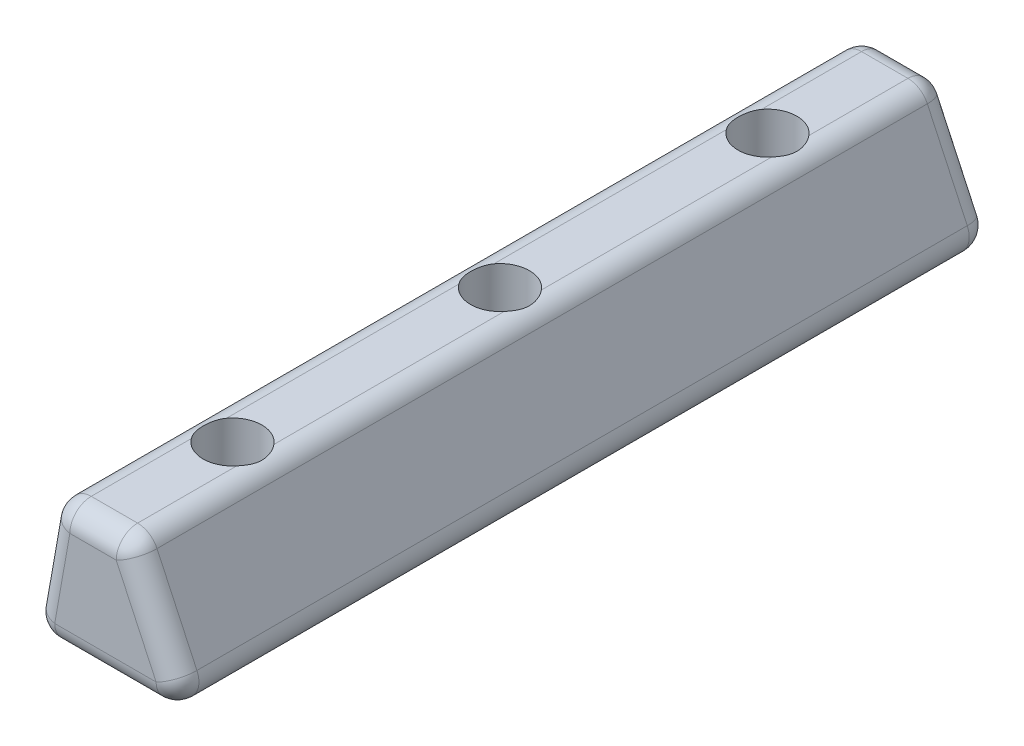
SolidWorks part; units mm, degrees
material "ABS"
ref_plane "前视基准面" through (0, 0, 0) normal (0, 0, 1) x (1, 0, 0)
ref_plane "上视基准面" through (0, 0, 0) normal (0, 1, 0) x (1, 0, 0)
ref_plane "右视基准面" through (0, 0, 0) normal (1, 0, 0) x (0, 0, -1)
other "Configuration Table"
sketch "草图1" plane through (0, 0, 0) normal (0, 0, 1) x (1, 0, 0)
  line L0 (0, 0) -> (15, 0)
  line L1 (15, 0) -> (9.4043, 12)
  line L2 (9.4043, 12) -> (2.1159, 12)
  line L3 (2.1159, 12) -> (0, 0)
  dimension "D1" = 15
  dimension "D2" = 80
  dimension "D3" = 65
  dimension "D4" = 12
extrude "凸台-拉伸1" add sketch "草图1" along normal blind 76
sketch "草图2" plane through (0, 0, 0) normal (0, -1, 0) x (1, 0, 0)
  line L0 (0, 38) -> (15, 38) construction
  line L3 (0, 76) -> (0, 0) construction
  line L6 (15, 76) -> (15, 0) construction
  circle A0 centre (6, 63) radius 1.55
  circle A1 centre (6, 13) radius 1.55
  circle A2 centre (6, 38) radius 1.55
  dimension "D1" = 3.1
  dimension "D2" = 3.1
  dimension "D3" = 3.1
  dimension "D4" = 25
  dimension "D5" = 25
  dimension "D6" = 6
  dimension "D7" = 6
  dimension "D8" = 6
extrude "切除-拉伸1" cut sketch "草图2" against normal through all
fillet "圆角1" radius 2 12 edges at (2.1159, 12, 38) (0, 0, 38) (15, 0, 38) (9.4043, 12, 38) (7.5, 0, 0) (12.2022, 6, 0) (5.7601, 12, 0) (1.058, 6, 0) (5.7601, 12, 76) (12.2022, 6, 76) (7.5, 0, 76) (1.058, 6, 76)
sketch "草图3" plane through (0, 12, 0) normal (0, 1, 0) x (1, 0, 0)
  circle A0 centre (6, -13) radius 2.75
  circle A1 centre (6, -38) radius 2.75
  circle A2 centre (6, -63) radius 2.75
  dimension "D1" = 5.5
  dimension "D2" = 5.5
  dimension "D3" = 5.5
extrude "切除-拉伸2" cut sketch "草图3" against normal blind 8
